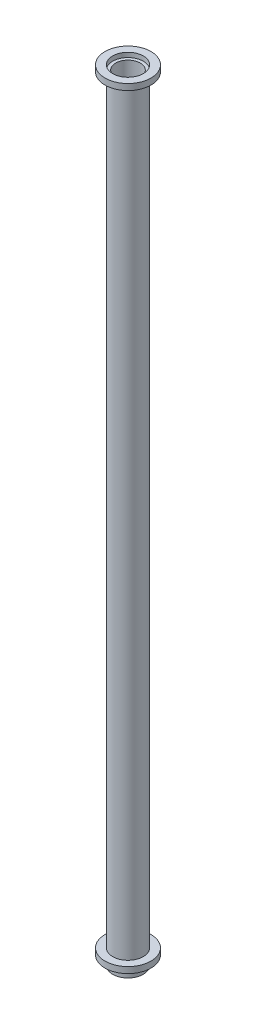
SolidWorks part; units mm, degrees
ref_plane "Front Plane" through (0, 0, 0) normal (0, 0, 1) x (1, 0, 0)
ref_plane "Top Plane" through (0, 0, 0) normal (0, 1, 0) x (1, 0, 0)
ref_plane "Right Plane" through (0, 0, 0) normal (1, 0, 0) x (0, 0, -1)
sketch "Sketch1" plane through (0, 0, 0) normal (0, 1, 0) x (1, 0, 0)
  circle A0 centre (0, 0) radius 10
  dimension "D1" = 20
extrude "Boss-Extrude1" add sketch "Sketch1" along normal blind 506
shell "Shell1" thickness 2
sketch "Sketch2" plane through (0, 506, 0) normal (0, 1, 0) x (1, 0, 0)
  circle A0 centre (0, 0) radius 15
  circle A1 centre (0, 0) radius 10 construction
  circle A2 centre (0, 0) radius 10
  dimension "D1" = 5
extrude "Boss-Extrude2" add sketch "Sketch2" along normal blind 3 and the other way blind 1
ref_plane "Plane1" through (0, 250, 0) normal (0, 1, 0) x (1, 0, 0)
pattern_linear "LPattern1" count 2 spacing 499 along (0, -1, 0) of "Boss-Extrude2"
